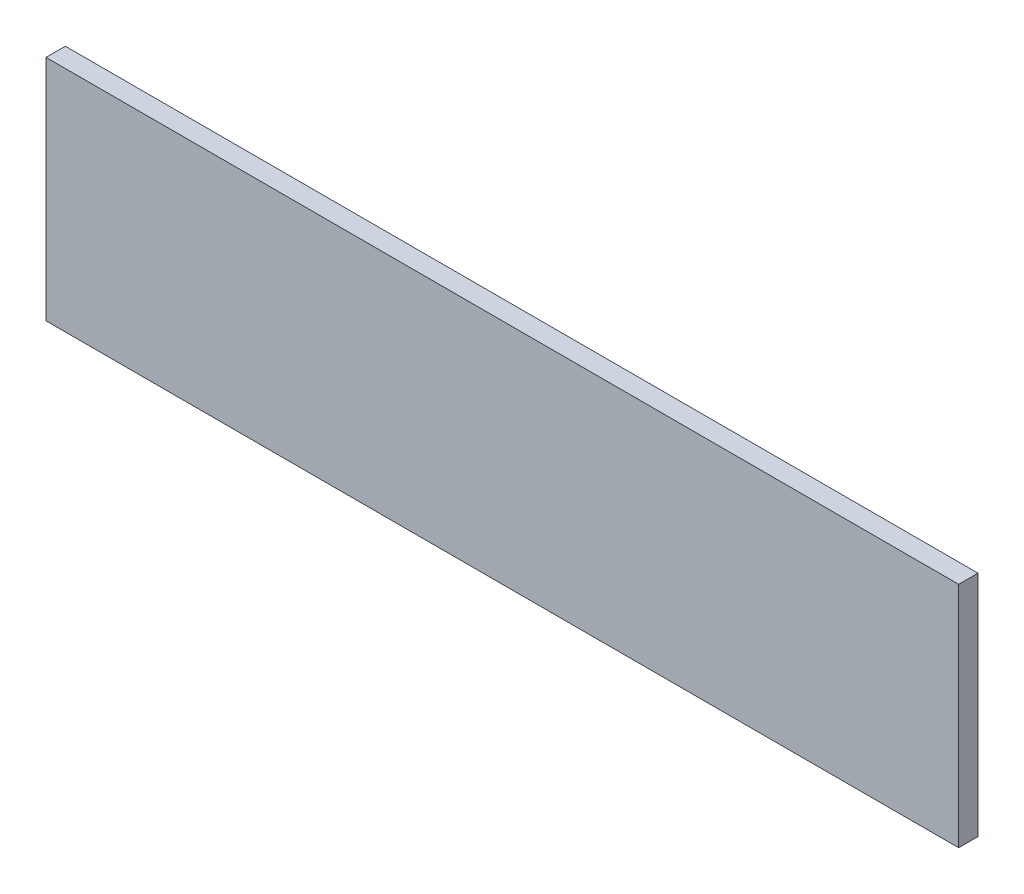
SolidWorks part; units mm, degrees
material "Aleación 1060"
ref_plane "Alzado" through (0, 0, 0) normal (0, 0, 1) x (1, 0, 0)
ref_plane "Planta" through (0, 0, 0) normal (0, 1, 0) x (1, 0, 0)
ref_plane "Vista lateral" through (0, 0, 0) normal (1, 0, 0) x (0, 0, -1)
sketch "Croquis1" plane through (0, 0, 0) normal (0, 0, 1) x (1, 0, 0)
  line L1 (-300, -75) -> (300, -75)
  line L2 (-300, -75) -> (-300, 75)
  line L3 (-300, 75) -> (300, 75)
  line L4 (300, -75) -> (300, 75)
  line L5 (-300, -75) -> (300, 75) construction
  line L6 (-300, 75) -> (300, -75) construction
  point P0 (0, 0)
  dimension "D1" = 150
  dimension "D2" = 600
extrude "Saliente-Extruir1" add sketch "Croquis1" along normal blind 12.7
